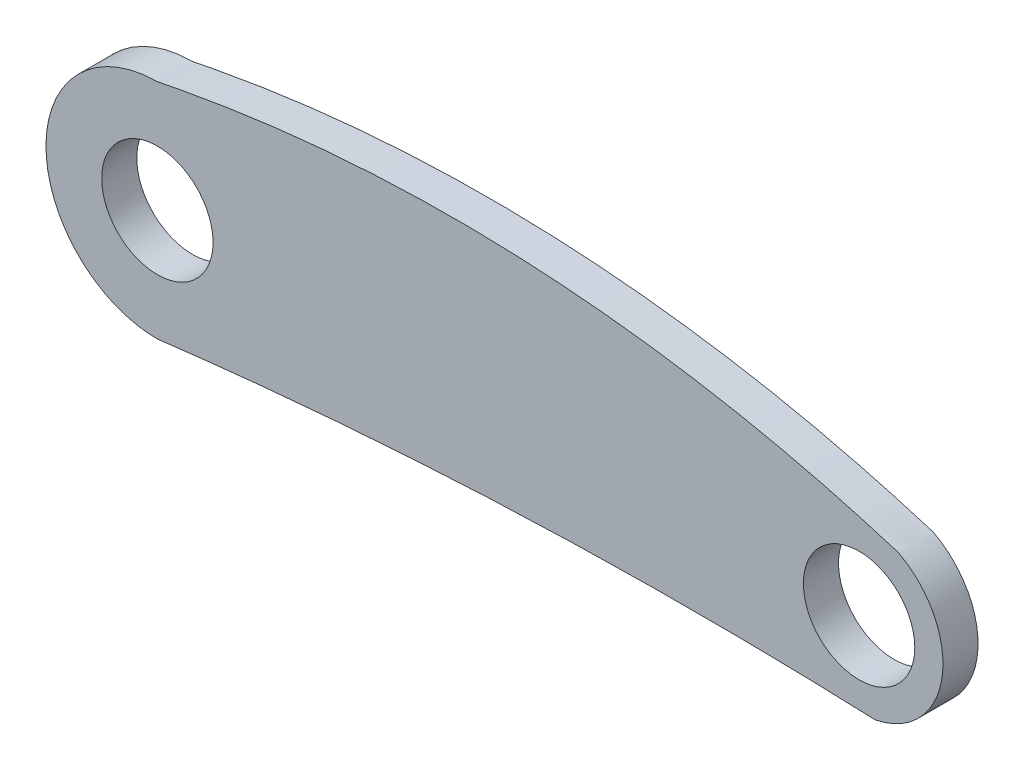
SolidWorks part; units mm, degrees
ref_plane "Alzado" through (0, 0, 0) normal (0, 0, 1) x (1, 0, 0)
ref_plane "Planta" through (0, 0, 0) normal (0, 1, 0) x (1, 0, 0)
ref_plane "Vista lateral" through (0, 0, 0) normal (1, 0, 0) x (0, 0, -1)
sketch "Croquis1" plane through (0, 0, 0) normal (0, 0, 1) x (1, 0, 0)
  line L0 (-6.35, 0) -> (13.3081, 0) construction
  line L1 (36.825, 0) -> (40, 0) construction
  arc A0 (0, 6.35) -> (0, -6.35) centre (0, 0) ccw construction
  arc A1 (40.912, -4.6941) -> (42.2329, 4.2285) centre (40, 0) ccw construction
  circle A2 centre (40, 0) radius 3.175
  arc A3 (42.2329, 4.2285) -> (0, 6.35) centre (16.9919, -76.8187) ccw construction
  arc A4 (40.912, -4.6941) -> (0, -6.35) centre (30.6055, -256.281) ccw construction
  circle A5 centre (0, 0) radius 3.175
  spline S0 degree 3 poles (40.9119, -4.6941) (27.2448, -4.1342) (13.5774, -4.6874) (0.0003, -6.35) (0.0002, -6.35) (0.0001, -6.35) (-0.0001, -6.35) (-0.0002, -6.35) (-0.0003, -6.35) (-12.6992, -6.3494) (-12.6991, 6.3495) (-0.0003, 6.35) (-0.0002, 6.35) (-0.0001, 6.35) (0.0001, 6.35) (0.0002, 6.35) (0.0003, 6.3501) (14.1066, 9.232) (28.4862, 8.5097) (42.2327, 4.2286) (42.2328, 4.2286) (42.2328, 4.2285) (42.233, 4.2285) (42.233, 4.2285) (42.2331, 4.2284) (47.0236, 1.6985) (46.2302, -3.6606) (40.9122, -4.694) (40.9122, -4.6941) (40.9121, -4.6941) (40.912, -4.6941) (40.9119, -4.6941) (40.9119, -4.6941) (27.2448, -4.1342) (13.5774, -4.6874) knots -0.000001 0 0 0 0.39013 0.39013 0.39013 0.390132 0.390134 0.390136 0.390136 0.390136 0.511143 0.511143 0.511143 0.511145 0.511146 0.511148 0.511148 0.511148 0.914052 0.914052 0.914052 0.914053 0.914054 0.914055 0.914055 0.914055 0.999996 0.999996 0.999996 0.999998 0.999999 1 1 1 1.39013 1.39013 1.39013 weights 1 0.997793 0.997793 1 1 1 1 1 1 0.333364 0.333364 1 1 1 1 1 1 0.97899 0.97899 1 1 1 1 1 1 0.554974 0.554974 1 1 1 1 1 1 0.997793 0.997793 only from (40.9119, -4.6941) to (40.9119, -4.6941)
  dimension "D1" = 12.7
  dimension "D2" = 6.35
  dimension "D3" = 6.35
  dimension "D4" = 40
extrude "Saliente-Extruir1" add sketch "Croquis1" along normal blind 2
